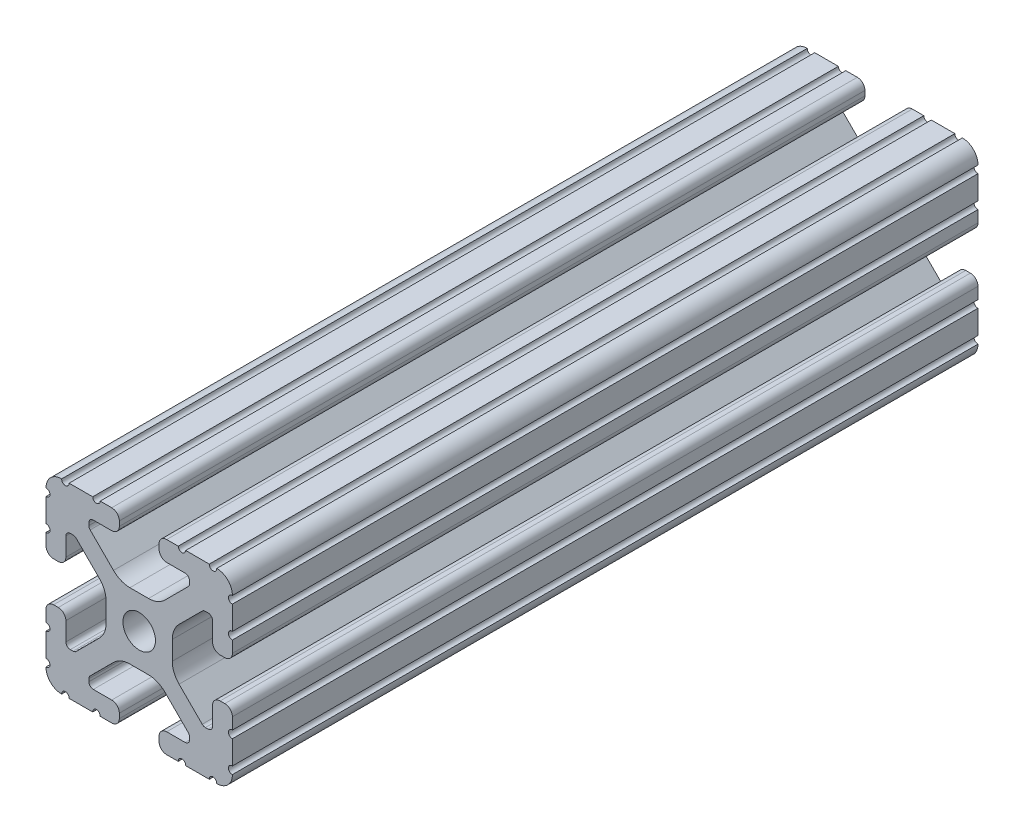
SolidWorks part; units mm, degrees
material "AISI 1020"
ref_plane "Front Plane" through (0, 0, 0) normal (0, 0, 1) x (1, 0, 0)
ref_plane "Top Plane" through (0, 0, 0) normal (0, 1, 0) x (1, 0, 0)
ref_plane "Right Plane" through (0, 0, 0) normal (1, 0, 0) x (0, 0, -1)
ref_plane "Plane1" through (0, 0, -304.8) normal (0, 0, -1) x (-1, 0, 0)
sketch "Sketch1" plane through (0, 0, -304.8) normal (0, 0, -1) x (-1, 0, 0)
  line L0 (14.3277, 19.05) -> (9.4982, 19.05)
  line L1 (7.9742, 19.05) -> (5.6176, 19.05)
  line L2 (4.064, 17.4964) -> (4.064, 16.5396)
  line L3 (5.6176, 14.986) -> (9.3853, 14.986)
  line L4 (10.287, 14.0843) -> (10.287, 13.5524)
  line L5 (10.0229, 12.9148) -> (5.2522, 8.144)
  line L6 (1.9022, 6.7564) -> (-1.9022, 6.7564)
  line L7 (-5.2522, 8.144) -> (-10.0229, 12.9148)
  line L8 (-10.287, 13.5524) -> (-10.287, 14.0843)
  line L9 (-9.3853, 14.986) -> (-5.6176, 14.986)
  line L10 (-4.064, 16.5396) -> (-4.064, 17.4964)
  line L11 (-5.6176, 19.05) -> (-7.9742, 19.05)
  line L12 (-9.4982, 19.05) -> (-14.3277, 19.05)
  line L13 (-19.05, 14.3277) -> (-19.05, 9.4961)
  line L14 (-19.05, 7.9763) -> (-19.05, 5.6176)
  line L15 (-17.4964, 4.064) -> (-16.5396, 4.064)
  line L16 (-14.986, 5.6176) -> (-14.986, 9.3853)
  line L17 (-14.0843, 10.287) -> (-13.516, 10.287)
  line L18 (-12.8784, 10.0229) -> (-8.1476, 5.2921)
  line L19 (-6.7564, 1.9335) -> (-6.7564, -1.9335)
  line L20 (-8.1476, -5.2921) -> (-12.8784, -10.0229)
  line L21 (-13.516, -10.287) -> (-14.0843, -10.287)
  line L22 (-14.986, -9.3853) -> (-14.986, -5.6176)
  line L23 (-16.5396, -4.064) -> (-17.4964, -4.064)
  line L24 (-19.05, -5.6176) -> (-19.05, -7.9763)
  line L25 (-19.05, -9.4961) -> (-19.05, -14.3277)
  line L26 (-14.3277, -19.05) -> (-9.4961, -19.05)
  line L27 (-7.9763, -19.05) -> (-5.6176, -19.05)
  line L28 (-4.064, -17.4964) -> (-4.064, -16.5396)
  line L29 (-5.6176, -14.986) -> (-9.3853, -14.986)
  line L30 (-10.287, -14.0843) -> (-10.287, -13.5524)
  line L31 (-10.0229, -12.9148) -> (-5.2522, -8.144)
  line L32 (-1.9022, -6.7564) -> (1.9022, -6.7564)
  line L33 (5.2522, -8.144) -> (10.0229, -12.9148)
  line L34 (10.287, -13.5524) -> (10.287, -14.0843)
  line L35 (9.3853, -14.986) -> (5.6176, -14.986)
  line L36 (4.064, -16.5396) -> (4.064, -17.4964)
  line L37 (5.6176, -19.05) -> (7.9763, -19.05)
  line L38 (9.4961, -19.05) -> (14.3277, -19.05)
  line L39 (19.05, -14.3277) -> (19.05, -9.4961)
  line L40 (19.05, -7.9763) -> (19.05, -5.6176)
  line L41 (17.4964, -4.064) -> (16.5396, -4.064)
  line L42 (14.986, -5.6176) -> (14.986, -9.3853)
  line L43 (14.0843, -10.287) -> (13.516, -10.287)
  line L44 (12.8784, -10.0229) -> (8.1476, -5.2921)
  line L45 (6.7564, -1.9335) -> (6.7564, 1.9335)
  line L46 (8.1476, 5.2921) -> (12.8784, 10.0229)
  line L47 (13.516, 10.287) -> (14.0843, 10.287)
  line L48 (14.986, 9.3853) -> (14.986, 5.6176)
  line L49 (16.5396, 4.064) -> (17.4964, 4.064)
  line L50 (19.05, 5.6176) -> (19.05, 7.9763)
  line L51 (19.05, 9.4961) -> (19.05, 14.3277)
  line L52 (19.05, 5.6176) -> (17.4964, 5.6176) construction
  line L53 (17.4964, 5.6176) -> (17.4964, 4.064) construction
  line L54 (17.4964, 5.6176) -> (18.5393, 4.466) construction
  arc A0 (15.8475, 19.05) -> (14.3277, 19.05) centre (15.0876, 18.9933) cw
  arc A1 (9.4982, 19.05) -> (7.9742, 19.05) centre (8.7362, 19.05) cw
  arc A2 (5.6176, 19.05) -> (4.064, 17.4964) centre (5.6176, 17.4964) ccw
  arc A3 (4.064, 16.5396) -> (5.6176, 14.986) centre (5.6176, 16.5396) ccw
  arc A4 (9.3853, 14.986) -> (10.287, 14.0843) centre (9.3853, 14.0843) cw
  arc A5 (10.287, 13.5524) -> (10.0229, 12.9148) centre (9.3853, 13.5524) cw
  arc A6 (5.2522, 8.144) -> (1.9022, 6.7564) centre (1.9022, 11.494) cw
  arc A7 (-1.9022, 6.7564) -> (-5.2522, 8.144) centre (-1.9022, 11.494) cw
  arc A8 (-10.0229, 12.9148) -> (-10.287, 13.5524) centre (-9.3853, 13.5524) cw
  arc A9 (-10.287, 14.0843) -> (-9.3853, 14.986) centre (-9.3853, 14.0843) cw
  arc A10 (-5.6176, 14.986) -> (-4.064, 16.5396) centre (-5.6176, 16.5396) ccw
  arc A11 (-4.064, 17.4964) -> (-5.6176, 19.05) centre (-5.6176, 17.4964) ccw
  arc A12 (-7.9742, 19.05) -> (-9.4982, 19.05) centre (-8.7362, 19.05) cw
  arc A13 (-14.3277, 19.05) -> (-15.8475, 19.05) centre (-15.0876, 18.9933) cw
  arc A14 (-15.8475, 19.05) -> (-19.05, 15.8475) centre (-15.8751, 15.8751) ccw
  arc A15 (-19.05, 15.8475) -> (-19.05, 14.3277) centre (-18.9933, 15.0876) cw
  arc A16 (-19.05, 9.4961) -> (-19.05, 7.9763) centre (-18.9933, 8.7362) cw
  arc A17 (-19.05, 5.6176) -> (-17.4964, 4.064) centre (-17.4964, 5.6176) ccw
  arc A18 (-16.5396, 4.064) -> (-14.986, 5.6176) centre (-16.5396, 5.6176) ccw
  arc A19 (-14.986, 9.3853) -> (-14.0843, 10.287) centre (-14.0843, 9.3853) cw
  arc A20 (-13.516, 10.287) -> (-12.8784, 10.0229) centre (-13.516, 9.3853) cw
  arc A21 (-8.1476, 5.2921) -> (-6.7564, 1.9335) centre (-11.5062, 1.9335) cw
  arc A22 (-6.7564, -1.9335) -> (-8.1476, -5.2921) centre (-11.5062, -1.9335) cw
  arc A23 (-12.8784, -10.0229) -> (-13.516, -10.287) centre (-13.516, -9.3853) cw
  arc A24 (-14.0843, -10.287) -> (-14.986, -9.3853) centre (-14.0843, -9.3853) cw
  arc A25 (-14.986, -5.6176) -> (-16.5396, -4.064) centre (-16.5396, -5.6176) ccw
  arc A26 (-17.4964, -4.064) -> (-19.05, -5.6176) centre (-17.4964, -5.6176) ccw
  arc A27 (-19.05, -7.9763) -> (-19.05, -9.4961) centre (-18.9933, -8.7362) cw
  arc A28 (-19.05, -14.3277) -> (-19.05, -15.8475) centre (-18.9933, -15.0876) cw
  arc A29 (-19.05, -15.8475) -> (-15.8475, -19.05) centre (-15.8751, -15.8751) ccw
  arc A30 (-15.8475, -19.05) -> (-14.3277, -19.05) centre (-15.0876, -18.9933) cw
  arc A31 (-9.4961, -19.05) -> (-7.9763, -19.05) centre (-8.7362, -18.9933) cw
  arc A32 (-5.6176, -19.05) -> (-4.064, -17.4964) centre (-5.6176, -17.4964) ccw
  arc A33 (-4.064, -16.5396) -> (-5.6176, -14.986) centre (-5.6176, -16.5396) ccw
  arc A34 (-9.3853, -14.986) -> (-10.287, -14.0843) centre (-9.3853, -14.0843) cw
  arc A35 (-10.287, -13.5524) -> (-10.0229, -12.9148) centre (-9.3853, -13.5524) cw
  arc A36 (-5.2522, -8.144) -> (-1.9022, -6.7564) centre (-1.9022, -11.494) cw
  arc A37 (1.9022, -6.7564) -> (5.2522, -8.144) centre (1.9022, -11.494) cw
  arc A38 (10.0229, -12.9148) -> (10.287, -13.5524) centre (9.3853, -13.5524) cw
  arc A39 (10.287, -14.0843) -> (9.3853, -14.986) centre (9.3853, -14.0843) cw
  arc A40 (5.6176, -14.986) -> (4.064, -16.5396) centre (5.6176, -16.5396) ccw
  arc A41 (4.064, -17.4964) -> (5.6176, -19.05) centre (5.6176, -17.4964) ccw
  arc A42 (7.9763, -19.05) -> (9.4961, -19.05) centre (8.7362, -18.9933) cw
  arc A43 (14.3277, -19.05) -> (15.8475, -19.05) centre (15.0876, -18.9933) cw
  arc A44 (15.8475, -19.05) -> (19.05, -15.8475) centre (15.8751, -15.8751) ccw
  arc A45 (19.05, -15.8475) -> (19.05, -14.3277) centre (18.9933, -15.0876) cw
  arc A46 (19.05, -9.4961) -> (19.05, -7.9763) centre (18.9933, -8.7362) cw
  arc A47 (19.05, -5.6176) -> (17.4964, -4.064) centre (17.4964, -5.6176) ccw
  arc A48 (16.5396, -4.064) -> (14.986, -5.6176) centre (16.5396, -5.6176) ccw
  arc A49 (14.986, -9.3853) -> (14.0843, -10.287) centre (14.0843, -9.3853) cw
  arc A50 (13.516, -10.287) -> (12.8784, -10.0229) centre (13.516, -9.3853) cw
  arc A51 (8.1476, -5.2921) -> (6.7564, -1.9335) centre (11.5062, -1.9335) cw
  arc A52 (6.7564, 1.9335) -> (8.1476, 5.2921) centre (11.5062, 1.9335) cw
  arc A53 (12.8784, 10.0229) -> (13.516, 10.287) centre (13.516, 9.3853) cw
  arc A54 (14.0843, 10.287) -> (14.986, 9.3853) centre (14.0843, 9.3853) cw
  arc A55 (14.986, 5.6176) -> (16.5396, 4.064) centre (16.5396, 5.6176) ccw
  arc A56 (17.4964, 4.064) -> (19.05, 5.6176) centre (17.4964, 5.6176) ccw
  arc A57 (19.05, 7.9763) -> (19.05, 9.4961) centre (18.9933, 8.7362) cw
  arc A58 (19.05, 14.3277) -> (19.05, 15.8475) centre (18.9933, 15.0876) cw
  arc A59 (19.05, 15.8475) -> (15.8475, 19.05) centre (15.8751, 15.8751) ccw
  circle A60 centre (0, 0) radius 3.3274
sketch "Sketch2" plane through (0, 0, 0) normal (0, 1, 0) x (1, 0, 0)
  line L1 (0, 152.4) -> (0, 304.8)
sweep "Sweep4" add profiles "Sketch1" path "Sketch2"
